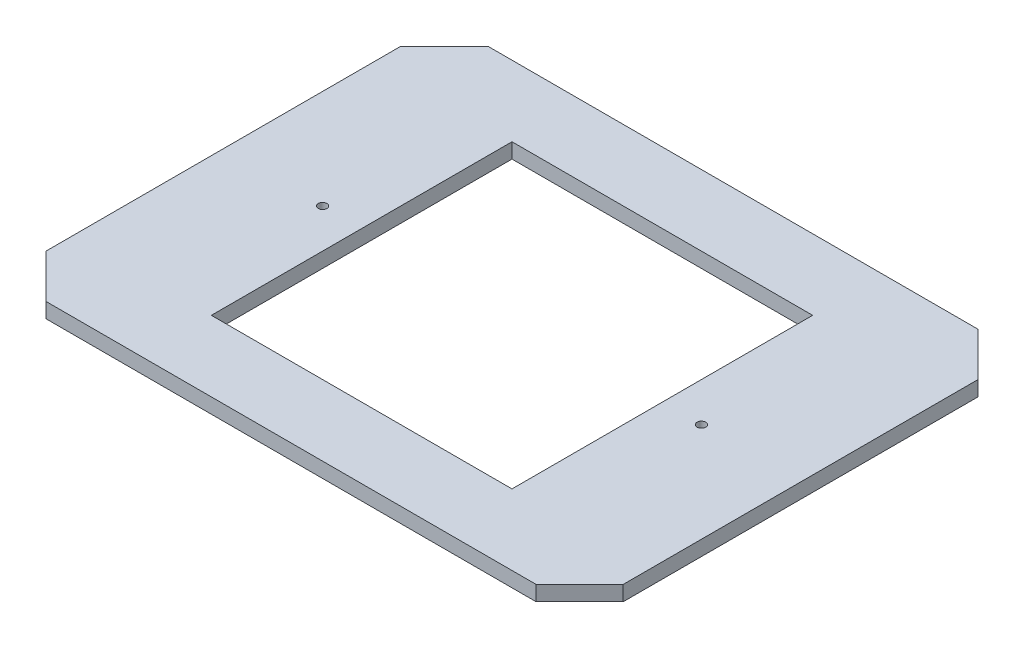
SolidWorks part; units mm, degrees
ref_plane "Alzado" through (0, 0, 0) normal (0, 0, 1) x (1, 0, 0)
ref_plane "Planta" through (0, 0, 0) normal (0, 1, 0) x (1, 0, 0)
ref_plane "Vista lateral" through (0, 0, 0) normal (1, 0, 0) x (0, 0, -1)
sketch "Croquis1" plane through (0, 0, 0) normal (0, 1, 0) x (1, 0, 0)
  line L0 (0, 0) -> (-14.5, 14.5)
  line L1 (-14.5, 14.5) -> (-14.5, 132.5)
  line L2 (-14.5, 132.5) -> (0, 147)
  line L3 (0, 147) -> (163, 147)
  line L4 (163, 147) -> (177.5, 132.5)
  line L5 (177.5, 132.5) -> (177.5, 14.5)
  line L6 (177.5, 14.5) -> (163, 0)
  line L7 (163, 0) -> (0, 0)
  line L8 (81.5, 0) -> (81.5, 147) construction
  line L9 (-14.5, 73.5) -> (177.5, 73.5) construction
  line L11 (31.5, 23.5) -> (131.5, 23.5)
  line L12 (31.5, 23.5) -> (31.5, 123.5)
  line L13 (31.5, 123.5) -> (131.5, 123.5)
  line L14 (131.5, 23.5) -> (131.5, 123.5)
  line L15 (31.5, 23.5) -> (131.5, 123.5) construction
  line L16 (31.5, 123.5) -> (131.5, 23.5) construction
  circle A0 centre (18.5, 73.5) radius 1.45
  circle A1 centre (144.5, 73.5) radius 1.45
  point P13 (81.5, 73.5)
  point P14 (81.5, 73.5)
  point P15 (81.5, 73.5)
  dimension "D5" = 13
  dimension "D6" = 2.9
  dimension "D1" = 163
  dimension "D2" = 118
  dimension "D3" = 147
  dimension "D4" = 100
  dimension "D7" = 13
extrude "Saliente-Extruir1" add sketch "Croquis1" along normal blind 5
